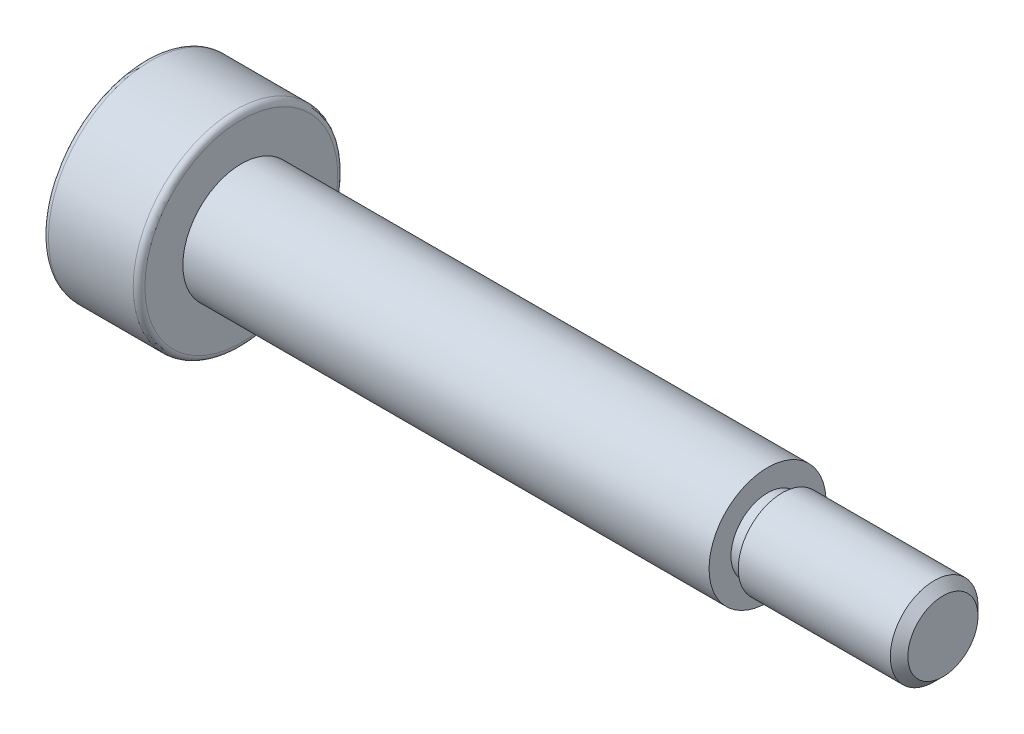
SolidWorks part; units mm, degrees
ref_plane "前视基准面" through (0, 0, 0) normal (0, 0, 1) x (1, 0, 0)
ref_plane "上视基准面" through (0, 0, 0) normal (0, 1, 0) x (1, 0, 0)
ref_plane "右视基准面" through (0, 0, 0) normal (1, 0, 0) x (0, 0, -1)
sketch "草图1" plane through (0, 0, 0) normal (0, 0, 1) x (1, 0, 0)
  line L0 (-13.65, 0) -> (13.65, 0) construction
  line L1 (-13.65, 0) -> (-13.65, 3.5)
  line L2 (-13.65, 3.5) -> (-10.35, 3.5)
  line L3 (-10.35, 3.5) -> (-10.35, 2)
  line L4 (-10.35, 2) -> (7.65, 2)
  line L5 (7.65, 2) -> (7.65, 1.5)
  line L6 (7.65, 1.5) -> (13.65, 1.5)
  line L7 (13.65, 1.5) -> (13.65, 0)
  line L8 (-13.65, 0) -> (13.65, 0)
  dimension "D1" = 4
  dimension "D2" = 7
  dimension "D3" = 3
  dimension "D4" = 6
  dimension "D5" = 18
  dimension "D6" = 3.3
revolve "旋转1" add sketch "草图1" angle 360 about L0
fillet "圆角1" radius 0.2 2 edges at (-10.35, 0, 3.5) (-13.65, 0, 3.5)
chamfer "倒角1" distance 0.3 angle 45 1 edges at (13.65, 0, 1.5)
sketch "草图3" plane through (0, 0, 0) normal (0, 0, 1) x (1, 0, 0)
  line L0 (7.65, 0) -> (13.35, 0) construction
  line L1 (7.65, -1.5) -> (7.65, 1.5) construction
  line L2 (13.35, 1.5) -> (13.35, -1.5) construction
  line L3 (7.65, -2) -> (7.65, 2) construction
  line L4 (7.65, 1.5) -> (8.15, 1.5)
  line L5 (7.65, 1.5) -> (7.65, 1.25)
  line L6 (7.65, 1.25) -> (8.15, 1.25)
  line L7 (8.15, 1.5) -> (8.15, 1.25)
  line L8 (13.35, 1.5) -> (7.65, 1.5) construction
  dimension "D1" = 2.5
  dimension "D2" = 0.5
revolve "切除-旋转1" cut sketch "草图3" angle 360 about L0
sketch "草图4" plane through (-13.65, 0, 0) normal (-1, 0, 0) x (0, 0, 1)
  line L1 (1.7321, 0) -> (0.866, 1.5)
  line L2 (0.866, 1.5) -> (-0.866, 1.5)
  line L3 (-0.866, 1.5) -> (-1.7321, 0)
  line L4 (-1.7321, 0) -> (-0.866, -1.5)
  line L5 (-0.866, -1.5) -> (0.866, -1.5)
  line L6 (0.866, -1.5) -> (1.7321, 0)
  circle A0 centre (0, 0) radius 1.5 construction
  dimension "D1" = 3
extrude "切除-拉伸1" cut sketch "草图4" against normal blind 2
